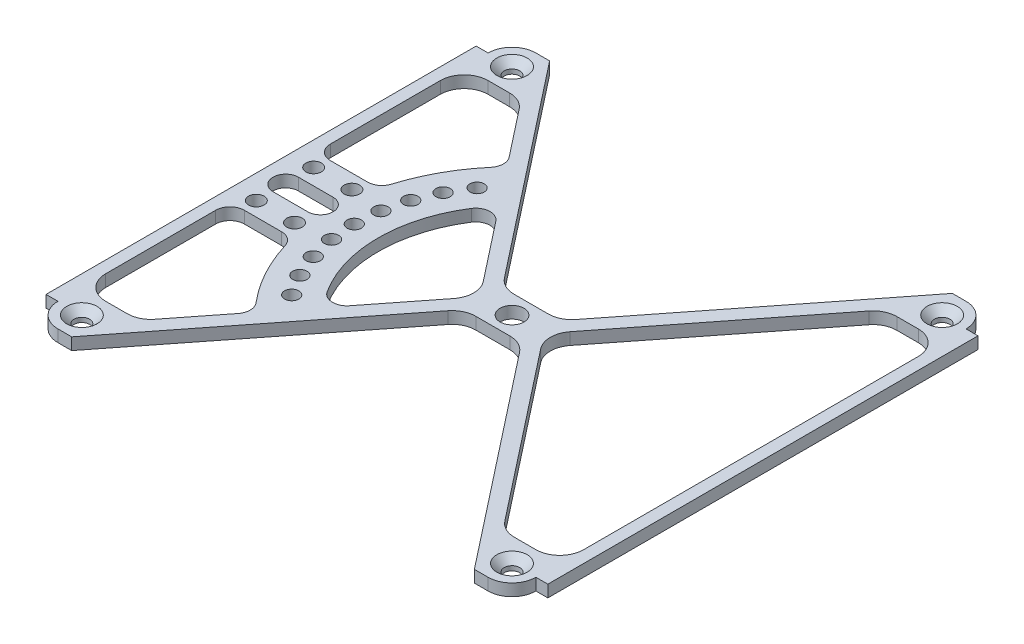
SolidWorks part; units mm, degrees
ref_plane "Front Plane" through (0, 0, 0) normal (0, 0, 1) x (1, 0, 0)
ref_plane "Top Plane" through (0, 0, 0) normal (0, 1, 0) x (1, 0, 0)
ref_plane "Right Plane" through (0, 0, 0) normal (1, 0, 0) x (0, 0, -1)
sketch "Sketch1" plane through (0, 0, 0) normal (0, 1, 0) x (1, 0, 0)
  line L989 (-45, 45) -> (45, 45) construction
  line L1008 (-52.5, -52.5) -> (52.5, -52.5) construction
  line L1009 (-52.5, -52.5) -> (-52.5, 52.5) construction
  line L1028 (-52.5, 52.5) -> (52.5, 52.5) construction
  line L1029 (52.5, -52.5) -> (52.5, 52.5) construction
  line L1030 (-52.5, -52.5) -> (52.5, 52.5) construction
  line L1031 (-52.5, 52.5) -> (52.5, -52.5) construction
  line L1032 (45, 45) -> (45, -45) construction
  line L1033 (45, -45) -> (-45, -45) construction
  line L1034 (-45, -45) -> (-45, 45) construction
  line L1035 (-52.5, 45) -> (-52.5, -45)
  line L1036 (-50, 45) -> (-52.5, 45)
  line L1037 (-50, 40) -> (-50, -40)
  line L1038 (-52.5, 0) -> (-50, 0) construction
  line L1039 (-45, 50) -> (-42.1272, 50)
  line L1040 (-42.1272, 50) -> (-6, 4)
  line L1041 (-6, 4) -> (6, 4)
  line L1042 (-38.088, 40) -> (-6.6731, 0)
  line L1043 (-32.12, 32.401) -> (-29.7607, 34.254) construction
  line L1044 (-50, 40) -> (-38.088, 40)
  line L1045 (-6.6731, 0) -> (0, 0) construction
  line L1046 (-55, 0) -> (55, 0) construction
  line L1047 (-50, -40) -> (-38.088, -40)
  line L1048 (-6, -4) -> (6, -4)
  line L1049 (-42.1272, -50) -> (-6, -4)
  line L1050 (-38.088, -40) -> (-6.6731, 0)
  line L1051 (-45, -50) -> (-42.1272, -50)
  line L1052 (-50, -45) -> (-52.5, -45)
  line L1053 (0, -55) -> (0, 55) construction
  line L1054 (45, -50) -> (42.1272, -50)
  line L1055 (50, -45) -> (52.5, -45)
  line L1056 (50, -40) -> (38.088, -40)
  line L1057 (38.088, -40) -> (6.6731, 0)
  line L1058 (42.1272, -50) -> (6, -4)
  line L1059 (38.088, 40) -> (6.6731, 0)
  line L1060 (42.1272, 50) -> (6, 4)
  line L1061 (45, 50) -> (42.1272, 50)
  line L1062 (50, 45) -> (52.5, 45)
  line L1063 (50, 40) -> (38.088, 40)
  line L1064 (50, 40) -> (50, -40)
  line L1065 (52.5, 45) -> (52.5, -45)
  circle A0 centre (-45, 45) radius 1.625
  circle A1 centre (45, 45) radius 1.625
  circle A2 centre (-45, -45) radius 1.625
  circle A3 centre (45, -45) radius 1.625
  arc A4 (-45, 50) -> (-50, 45) centre (-45, 45) ccw
  arc A8 (-45, -50) -> (-50, -45) centre (-45, -45) cw
  arc A9 (45, -50) -> (50, -45) centre (45, -45) ccw
  arc A10 (45, 50) -> (50, 45) centre (45, 45) cw
  circle A11 centre (0, 0) radius 2.5
  point P0 (0, 0)
  dimension "D5" = 2.5
  dimension "D6" = 3
  dimension "D8" = 12
  dimension "D7" = 5
  dimension "D2" = 90
  dimension "D3" = 3.25
  dimension "D4" = 5
  dimension "D10" = 5
  dimension "D1" = 105
  dimension "D9" = 8
extrude "Boss-Extrude1" add sketch "Sketch1" along normal blind 2.5
fillet "Fillet1" radius 5 6 edges at (6, 1.25, 4) (-6, 1.25, 4) (6, 1.25, -4) (-6, 1.25, -4) (6.6731, 1.25, 0) (-6.6731, 1.25, 0)
fillet "Fillet2" radius 5 8 edges at (50, 1.25, -40) (38.088, 1.25, -40) (38.088, 1.25, 40) (50, 1.25, 40) (-38.088, 1.25, 40) (-50, 1.25, 40) (-38.088, 1.25, -40) (-50, 1.25, -40)
chamfer "Chamfer1" distance 1.55 angle 45 4 edges at (-45, 2.5, 46.625) (45, 2.5, 46.625) (45, 2.5, -43.375) (-45, 2.5, -43.375)
sketch "Sketch3" plane through (0, 2.5, 0) normal (0, 1, 0) x (1, 0, 0)
  line L0 (-9.0986, 3.0883) -> (-36.5866, 38.0883) construction
  line L1 (-36.5866, -38.0883) -> (-9.0986, -3.0883) construction
  line L2 (-27.3733, 26.3572) -> (-21.1152, 18.3888)
  line L3 (-21.1152, -18.3888) -> (-27.3733, -26.3572)
  line L4 (0, 0) -> (-52.5, 0) construction
  line L6 (-52.5, 9) -> (-52.5, -9)
  line L7 (-52.5, 9) -> (-36.9188, 9)
  line L8 (-52.5, -9) -> (-36.9188, -9)
  line L9 (-47.3538, 0) -> (-40.0798, 0) construction
  line L10 (-47.3538, 2.6462) -> (-40.0798, 2.6462)
  line L11 (-47.3538, -2.6462) -> (-40.0798, -2.6462)
  line L12 (-47.5, 6) -> (-39.5, 6) construction
  line L13 (-43.5, 6) -> (-43.5, 0) construction
  line L16 (-52.5, 45) -> (-52.5, -45) construction
  arc A0 (-27.3733, 26.3572) -> (-36.9188, 9) centre (0, 0) ccw
  arc A1 (-21.1152, 18.3888) -> (-21.1152, -18.3888) centre (0, 0) ccw
  arc A2 (-36.9188, -9) -> (-27.3733, -26.3572) centre (0, 0) ccw
  arc A3 (-47.3538, 2.6462) -> (-47.3538, -2.6462) centre (-47.3538, 0) ccw
  arc A4 (-40.0798, -2.6462) -> (-40.0798, 2.6462) centre (-40.0798, 0) ccw
  circle A5 centre (-47.5, 6) radius 1.625
  circle A6 centre (-39.5, 6) radius 1.625
  circle A7 centre (-39.5, -6) radius 1.625
  circle A8 centre (-47.5, -6) radius 1.625
  circle A9 centre (0, 0) radius 33 construction
  circle A10 centre (-33, 0) radius 1.5
  circle A11 centre (-32.5937, 5.1623) radius 1.5
  circle A12 centre (-31.3849, 10.1976) radius 1.5
  circle A13 centre (-29.4032, 14.9817) radius 1.5
  circle A14 centre (-26.6976, 19.3969) radius 1.5
  circle A15 centre (-23.3345, 23.3345) radius 1.5 [skipped]
  circle A16 centre (-19.3969, 26.6976) radius 1.5 [skipped]
  circle A17 centre (-14.9817, 29.4032) radius 1.5 [skipped]
  circle A18 centre (-10.1976, 31.3849) radius 1.5 [skipped]
  circle A19 centre (-5.1623, 32.5937) radius 1.5 [skipped]
  circle A20 centre (0, 33) radius 1.5 [skipped]
  circle A21 centre (5.1623, 32.5937) radius 1.5 [skipped]
  circle A22 centre (10.1976, 31.3849) radius 1.5 [skipped]
  circle A23 centre (14.9817, 29.4032) radius 1.5 [skipped]
  circle A24 centre (19.3969, 26.6976) radius 1.5 [skipped]
  circle A25 centre (23.3345, 23.3345) radius 1.5 [skipped]
  circle A26 centre (26.6976, 19.3969) radius 1.5 [skipped]
  circle A27 centre (29.4032, 14.9817) radius 1.5 [skipped]
  circle A28 centre (31.3849, 10.1976) radius 1.5 [skipped]
  circle A29 centre (32.5937, 5.1623) radius 1.5 [skipped]
  circle A30 centre (33, 0) radius 1.5 [skipped]
  circle A31 centre (32.5937, -5.1623) radius 1.5 [skipped]
  circle A32 centre (31.3849, -10.1976) radius 1.5 [skipped]
  circle A33 centre (29.4032, -14.9817) radius 1.5 [skipped]
  circle A34 centre (26.6976, -19.3969) radius 1.5 [skipped]
  circle A35 centre (23.3345, -23.3345) radius 1.5 [skipped]
  circle A36 centre (19.3969, -26.6976) radius 1.5 [skipped]
  circle A37 centre (14.9817, -29.4032) radius 1.5 [skipped]
  circle A38 centre (10.1976, -31.3849) radius 1.5 [skipped]
  circle A39 centre (5.1623, -32.5937) radius 1.5 [skipped]
  circle A40 centre (0, -33) radius 1.5 [skipped]
  circle A41 centre (-5.1623, -32.5937) radius 1.5 [skipped]
  circle A42 centre (-10.1976, -31.3849) radius 1.5 [skipped]
  circle A43 centre (-14.9817, -29.4032) radius 1.5 [skipped]
  circle A44 centre (-19.3969, -26.6976) radius 1.5 [skipped]
  circle A45 centre (-23.3345, -23.3345) radius 1.5 [skipped]
  circle A46 centre (-26.6976, -19.3969) radius 1.5
  circle A47 centre (-29.4032, -14.9817) radius 1.5
  circle A48 centre (-31.3849, -10.1976) radius 1.5
  circle A49 centre (-32.5937, -5.1623) radius 1.5
  point P20 (-43.7168, 0)
  point P38 (-52.5, 0)
  point P119 (0, 0)
  dimension "D1" = 38
  dimension "D2" = 28
  dimension "D4" = 3.25
  dimension "D8" = 33
  dimension "D9" = 3
  dimension "D3" = 18
  dimension "D5" = 8
  dimension "D6" = 6
  dimension "D7" = 9
  dimension "D10" = 40
extrude "Boss-Extrude2" add sketch "Sketch3" against normal up to surface (2.5 mm away) up to face at (45, 0, 46.625)
fillet "Fillet3" radius 3 8 edges at (-36.9188, 1.25, -9) (-21.1152, 1.25, -18.3888) (-27.3733, 1.25, -26.3572) (-21.1152, 1.25, 18.3888) (-27.3733, 1.25, 26.3572) (-36.9188, 1.25, 9) (-50, 1.25, 9) (-50, 1.25, -9)
